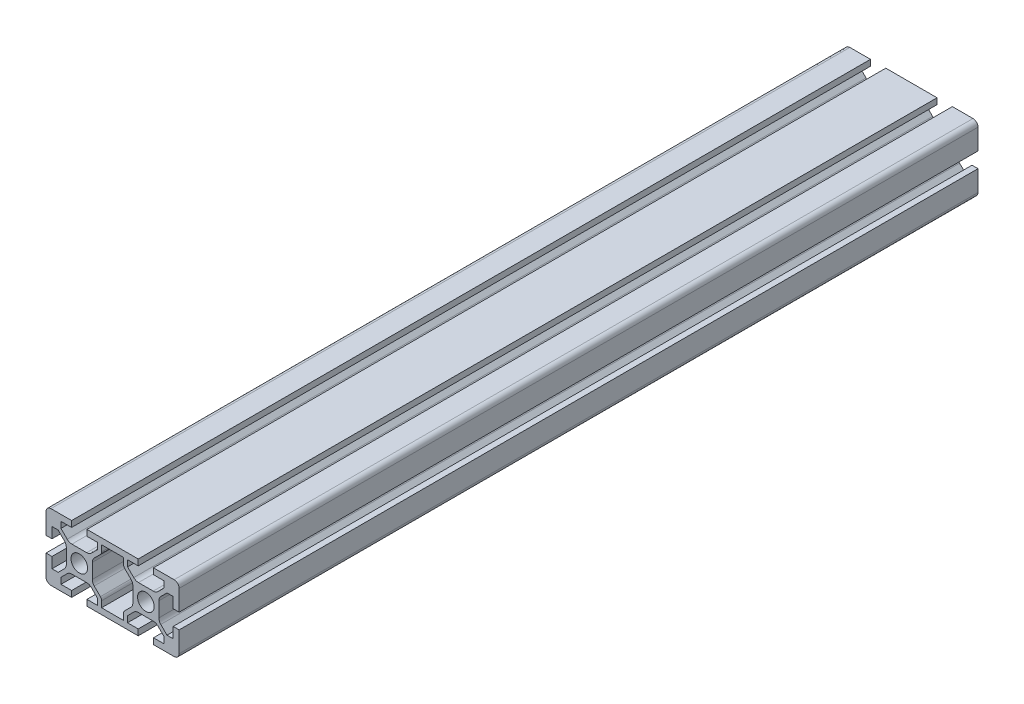
SolidWorks part; units mm, degrees
ref_plane "Alzado" through (0, 0, 0) normal (0, 0, 1) x (1, 0, 0)
ref_plane "Planta" through (0, 0, 0) normal (0, 1, 0) x (1, 0, 0)
ref_plane "Vista lateral" through (0, 0, 0) normal (1, 0, 0) x (0, 0, -1)
sketch "Croquis1" plane through (0, 0, 0) normal (0, 0, 1) x (1, 0, 0)
  line L0 (0, 0) -> (-10, 0) construction
  line L1 (-10, 0) -> (-10, 10) construction
  line L2 (-10, 10) -> (0, 10) construction
  line L3 (0, 10) -> (0, 0) construction
  line L4 (-10, 8.5) -> (-10, 2.3)
  line L5 (-8.2, 2.3) -> (-8.2, 5.5)
  line L6 (-6.3485, 5.5) -> (-4.4858, 3.6373)
  line L7 (-10, 10) -> (0, 0) construction
  line L8 (-3.9, 2.223) -> (-3.9, 0)
  line L9 (-8.2, 5.5) -> (-6.3485, 5.5)
  line L14 (-10, 2.3) -> (-8.2, 2.3)
  line L15 (-2.223, 3.9) -> (0, 3.9)
  line L16 (-5.5, 6.3485) -> (-3.6373, 4.4858)
  line L17 (-5.5, 8.2) -> (-5.5, 6.3485)
  line L18 (-2.3, 10) -> (-2.3, 8.2)
  line L19 (-2.3, 8.2) -> (-5.5, 8.2)
  line L20 (-8.5, 10) -> (-2.3, 10)
  line L22 (2.3, 10) -> (2.3, 8.2)
  line L23 (2.3, 8.2) -> (5.5, 8.2)
  line L24 (5.5, 8.2) -> (5.5, 6.3485)
  line L25 (5.5, 6.3485) -> (3.6373, 4.4858)
  line L26 (2.223, 3.9) -> (0, 3.9)
  line L27 (3.9, 2.223) -> (3.9, 0)
  line L37 (6.3339, -5.4854) -> (4.4858, -3.6373)
  line L38 (3.9, -2.223) -> (3.9, 0)
  line L39 (2.223, -3.9) -> (0, -3.9)
  line L40 (5.5, -6.3485) -> (3.6373, -4.4858)
  line L41 (5.5, -8.2) -> (5.5, -6.3485)
  line L42 (2.3, -8.2) -> (5.5, -8.2)
  line L43 (2.3, -10) -> (2.3, -8.2)
  line L45 (-8.5, -10) -> (-2.3, -10)
  line L46 (-2.3, -10) -> (-2.3, -8.2)
  line L47 (-2.3, -8.2) -> (-5.5, -8.2)
  line L48 (-5.5, -8.2) -> (-5.5, -6.3485)
  line L49 (-5.5, -6.3485) -> (-3.6373, -4.4858)
  line L50 (-2.223, -3.9) -> (0, -3.9)
  line L51 (-3.9, -2.223) -> (-3.9, 0)
  line L52 (-6.3485, -5.5) -> (-4.4858, -3.6373)
  line L53 (-8.2, -5.5) -> (-6.3485, -5.5)
  line L54 (-8.2, -2.3) -> (-8.2, -5.5)
  line L55 (-10, -2.3) -> (-8.2, -2.3)
  line L56 (-10, -8.5) -> (-10, -2.3)
  line L60 (16.1, 2.223) -> (16.1, 0)
  line L63 (17.777, 3.9) -> (20, 3.9)
  line L64 (14.5, 6.3485) -> (16.3627, 4.4858)
  line L65 (14.5, 8.2) -> (14.5, 6.3485)
  line L66 (17.7, 10) -> (17.7, 8.2)
  line L67 (17.7, 8.2) -> (14.5, 8.2)
  line L69 (28.5, 10) -> (22.3, 10)
  line L70 (22.3, 10) -> (22.3, 8.2)
  line L71 (22.3, 8.2) -> (25.5, 8.2)
  line L72 (25.5, 8.2) -> (25.5, 6.3485)
  line L73 (25.5, 6.3485) -> (23.6373, 4.4858)
  line L74 (22.223, 3.9) -> (20, 3.9)
  line L75 (23.9, 2.223) -> (23.9, 0)
  line L76 (26.3485, 5.5) -> (24.4858, 3.6373)
  line L77 (28.2, 5.5) -> (26.3485, 5.5)
  line L78 (28.2, 2.3) -> (28.2, 5.5)
  line L79 (30, 2.3) -> (28.2, 2.3)
  line L80 (30, 8.5) -> (30, 2.3)
  line L81 (30, -8.5) -> (30, -2.3)
  line L82 (30, -2.3) -> (28.2, -2.3)
  line L83 (28.2, -2.3) -> (28.2, -5.5)
  line L84 (28.2, -5.5) -> (26.3485, -5.5)
  line L85 (26.3485, -5.5) -> (24.4858, -3.6373)
  line L86 (23.9, -2.223) -> (23.9, 0)
  line L87 (22.223, -3.9) -> (20, -3.9)
  line L88 (25.5, -6.3485) -> (23.6373, -4.4858)
  line L89 (25.5, -8.2) -> (25.5, -6.3485)
  line L90 (22.3, -8.2) -> (25.5, -8.2)
  line L91 (22.3, -10) -> (22.3, -8.2)
  line L92 (28.5, -10) -> (22.3, -10)
  line L94 (17.7, -10) -> (17.7, -8.2)
  line L95 (17.7, -8.2) -> (14.5, -8.2)
  line L96 (14.5, -8.2) -> (14.5, -6.3485)
  line L97 (14.5, -6.3485) -> (16.3627, -4.4858)
  line L98 (17.777, -3.9) -> (20, -3.9)
  line L99 (16.1, -2.223) -> (16.1, 0)
  line L100 (13.6661, -5.4854) -> (15.5142, -3.6373)
  line L105 (2.3, -10) -> (17.7, -10)
  line L106 (6.7, -6.3692) -> (6.7, -8.2)
  line L107 (10, -8.5) -> (10, -2.3) [skipped]
  line L108 (10, -2.3) -> (8.2, -2.3) [skipped]
  line L109 (8.2, -2.3) -> (8.2, -5.5) [skipped]
  line L110 (8.2, -5.5) -> (6.3485, -5.5) [skipped]
  line L111 (8.5, -10) -> (2.3, -10) [skipped]
  line L112 (11.5, -10) -> (17.7, -10) [skipped]
  line L113 (11.8, -5.5) -> (13.6515, -5.5) [skipped]
  line L114 (11.8, -2.3) -> (11.8, -5.5) [skipped]
  line L115 (10, -2.3) -> (11.8, -2.3) [skipped]
  line L116 (10, -8.5) -> (10, -2.3) [skipped]
  line L117 (13.3, -6.3692) -> (13.3, -8.2)
  line L118 (6.7, -8.2) -> (13.3, -8.2)
  line L120 (8.5, 10) -> (2.3, 10) [skipped]
  line L121 (6.3485, 5.5) -> (4.4858, 3.6373) [skipped]
  line L122 (8.2, 5.5) -> (6.3485, 5.5) [skipped]
  line L123 (8.2, 2.3) -> (8.2, 5.5) [skipped]
  line L124 (10, 2.3) -> (8.2, 2.3) [skipped]
  line L125 (10, 8.5) -> (10, 2.3) [skipped]
  line L126 (10, 8.5) -> (10, 2.3) [skipped]
  line L127 (11.8, 2.3) -> (11.8, 5.5) [skipped]
  line L128 (13.6515, 5.5) -> (15.5142, 3.6373) [skipped]
  line L129 (11.8, 5.5) -> (13.6515, 5.5) [skipped]
  line L130 (10, 2.3) -> (11.8, 2.3) [skipped]
  line L131 (11.5, 10) -> (17.7, 10) [skipped]
  line L132 (13.6661, 5.4854) -> (15.5142, 3.6373)
  line L133 (13.3, 6.3692) -> (13.3, 8.2)
  line L134 (6.7, 8.2) -> (13.3, 8.2)
  line L135 (6.7, 6.3692) -> (6.7, 8.2)
  line L136 (2.3, 10) -> (17.7, 10)
  line L137 (6.3339, 5.4854) -> (4.4858, 3.6373)
  arc A0 (-8.5, 10) -> (-10, 8.5) centre (-8.5, 8.5) ccw
  arc A1 (0, 2.5) -> (-2.5, 0) centre (0, 0) ccw
  arc A2 (-3.9, 2.223) -> (-4.4858, 3.6373) centre (-5.9, 2.223) ccw
  arc A3 (-2.223, 3.9) -> (-3.6373, 4.4858) centre (-2.223, 5.9) cw
  arc A4 (2.223, 3.9) -> (3.6373, 4.4858) centre (2.223, 5.9) ccw
  arc A5 (2.5, 0) -> (0, 2.5) centre (0, 0) ccw
  arc A6 (3.9, 2.223) -> (4.4858, 3.6373) centre (5.9, 2.223) cw
  arc A8 (3.9, -2.223) -> (4.4858, -3.6373) centre (5.9, -2.223) ccw
  arc A9 (0, -2.5) -> (2.5, 0) centre (0, 0) ccw
  arc A10 (2.223, -3.9) -> (3.6373, -4.4858) centre (2.223, -5.9) cw
  arc A12 (-2.223, -3.9) -> (-3.6373, -4.4858) centre (-2.223, -5.9) ccw
  arc A13 (-2.5, 0) -> (0, -2.5) centre (0, 0) ccw
  arc A14 (-3.9, -2.223) -> (-4.4858, -3.6373) centre (-5.9, -2.223) cw
  arc A15 (-10, -8.5) -> (-8.5, -10) centre (-8.5, -8.5) ccw
  arc A17 (20, 2.5) -> (17.5, 0) centre (20, 0) ccw
  arc A18 (16.1, 2.223) -> (15.5142, 3.6373) centre (14.1, 2.223) ccw
  arc A19 (17.777, 3.9) -> (16.3627, 4.4858) centre (17.777, 5.9) cw
  arc A20 (22.223, 3.9) -> (23.6373, 4.4858) centre (22.223, 5.9) ccw
  arc A21 (22.5, 0) -> (20, 2.5) centre (20, 0) ccw
  arc A22 (23.9, 2.223) -> (24.4858, 3.6373) centre (25.9, 2.223) cw
  arc A23 (30, 8.5) -> (28.5, 10) centre (28.5, 8.5) ccw
  arc A24 (23.9, -2.223) -> (24.4858, -3.6373) centre (25.9, -2.223) ccw
  arc A25 (20, -2.5) -> (22.5, 0) centre (20, 0) ccw
  arc A26 (22.223, -3.9) -> (23.6373, -4.4858) centre (22.223, -5.9) cw
  arc A27 (28.5, -10) -> (30, -8.5) centre (28.5, -8.5) ccw
  arc A28 (17.777, -3.9) -> (16.3627, -4.4858) centre (17.777, -5.9) ccw
  arc A29 (17.5, 0) -> (20, -2.5) centre (20, 0) ccw
  arc A30 (16.1, -2.223) -> (15.5142, -3.6373) centre (14.1, -2.223) cw
  arc A32 (10, 8.5) -> (8.5, 10) centre (8.5, 8.5) ccw [skipped]
  arc A33 (11.5, 10) -> (10, 8.5) centre (11.5, 8.5) ccw [skipped]
  arc A34 (8.5, -10) -> (10, -8.5) centre (8.5, -8.5) ccw [skipped]
  arc A35 (10, -8.5) -> (11.5, -10) centre (11.5, -8.5) ccw [skipped]
  arc A38 (6.7, -6.3692) -> (6.3339, -5.4854) centre (5.45, -6.3692) ccw
  arc A39 (13.6661, -5.4854) -> (13.3, -6.3692) centre (14.55, -6.3692) ccw
  arc A40 (13.6661, 5.4854) -> (13.3, 6.3692) centre (14.55, 6.3692) cw
  arc A41 (6.7, 6.3692) -> (6.3339, 5.4854) centre (5.45, 6.3692) cw
  point P92 (0, 0)
  point P161 (20, 0)
  dimension "D3" = 3
  dimension "D9" = 2.5
  dimension "D10" = 2
  dimension "D15" = 2.5
  dimension "D16" = 2.5
  dimension "D2" = 10
  dimension "D4" = 6.2
  dimension "D5" = 1.8
  dimension "D6" = 0.6
  dimension "D7" = 6.1
  dimension "D8" = 5.5
  dimension "D13" = 1.2
  dimension "D14" = 1.2
  dimension "D12" = 2
  dimension "D11" = 4
extrude "Saliente-Extruir1" add sketch "Croquis1" along normal blind 240
